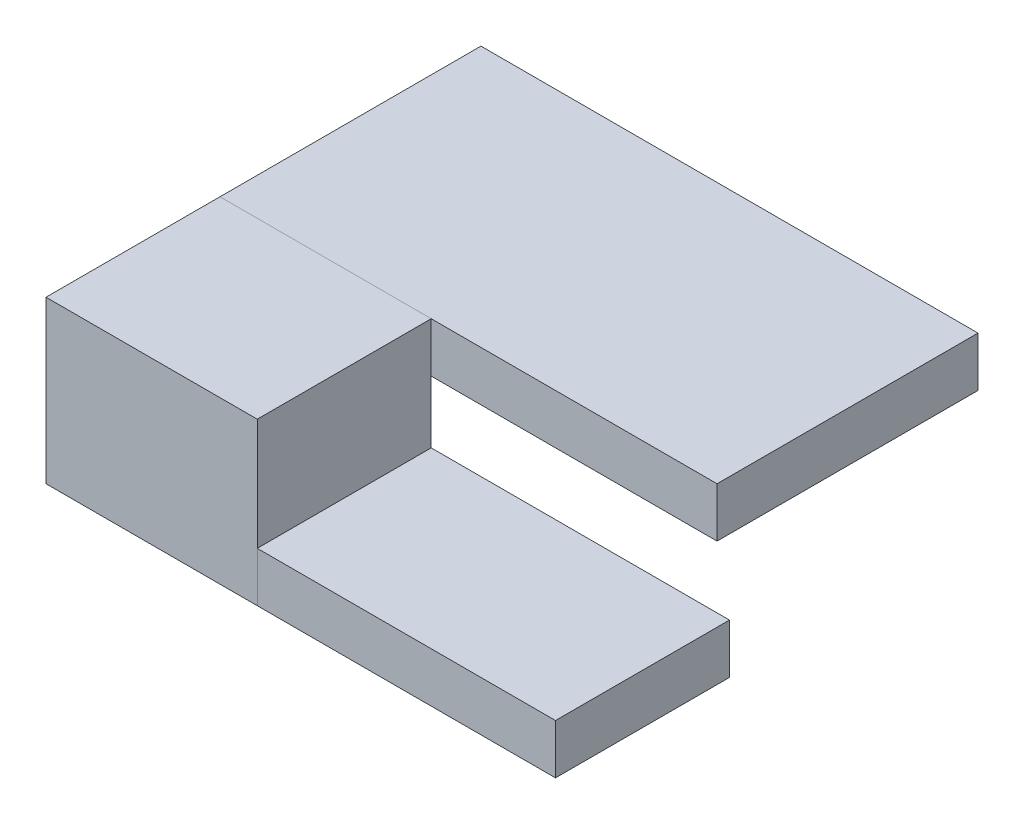
SolidWorks part; units mm, degrees
ref_plane "Front Plane" through (0, 0, 0) normal (0, 0, 1) x (1, 0, 0)
ref_plane "Top Plane" through (0, 0, 0) normal (0, 1, 0) x (1, 0, 0)
ref_plane "Right Plane" through (0, 0, 0) normal (1, 0, 0) x (0, 0, -1)
other "Configuration Table"
sketch "Sketch1" plane through (0, 0, 0) normal (1, 0, 0) x (0, 0, -1)
  line L1 (-491, -13) -> (-505, -13)
  line L2 (-491, -13) -> (-491, -9)
  line L3 (-491, -9) -> (-505, -9)
  line L4 (-505, -13) -> (-505, -9)
  line L5 (-491, -13) -> (-505, -9) construction
  line L6 (-491, -9) -> (-505, -13) construction
  point P0 (-498, -11)
extrude "anchor_plate" add sketch "Sketch1" along normal blind 24 from offset 17 separate body
sketch "Sketch2" plane through (0, 0, 0) normal (1, 0, 0) x (0, 0, -1)
  line L1 (-491, -13) -> (-505, -13)
  line L2 (-491, -13) -> (-491, 0)
  line L3 (-491, 0) -> (-505, 0)
  line L4 (-505, -13) -> (-505, 0)
  line L5 (-491, -13) -> (-505, 0) construction
  line L6 (-491, 0) -> (-505, -13) construction
  point P0 (-498, -6.5)
extrude "column" add sketch "Sketch2" along normal blind 17 from offset 0 separate body
sketch "Sketch3" plane through (0, 0, 0) normal (1, 0, 0) x (0, 0, -1)
  line L1 (-470, -4) -> (-491, -4)
  line L2 (-470, -4) -> (-470, 0)
  line L3 (-470, 0) -> (-491, 0)
  line L4 (-491, -4) -> (-491, 0)
  line L5 (-470, -4) -> (-491, 0) construction
  line L6 (-470, 0) -> (-491, -4) construction
  point P0 (-480.5, -2)
extrude "foot" add sketch "Sketch3" along normal blind 40 from offset 0 separate body
